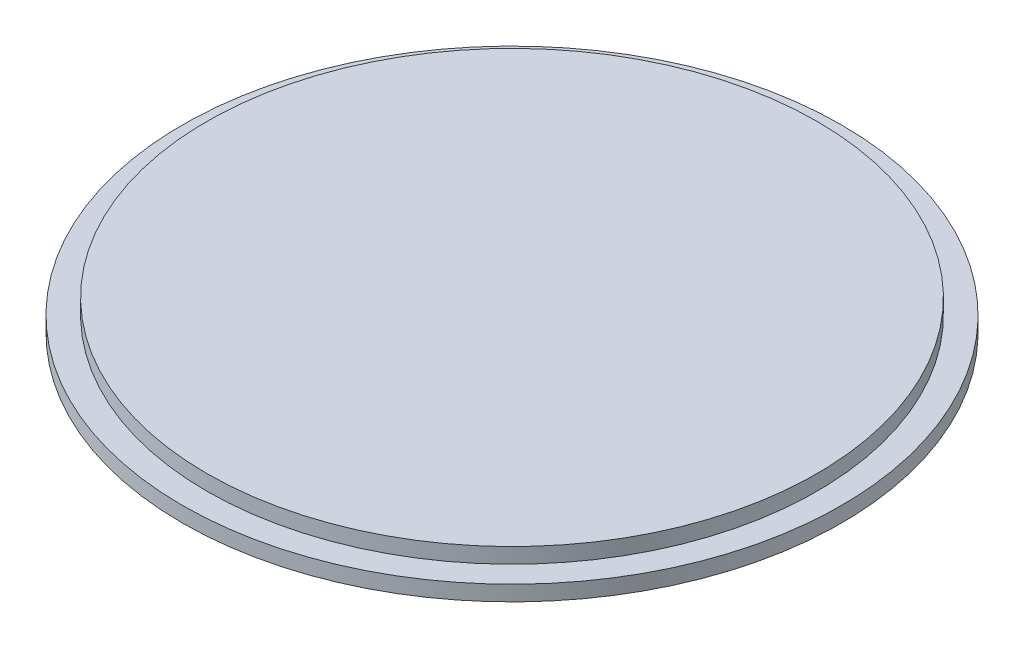
SolidWorks part; units mm, degrees
material "6061-T6 (SS)"
ref_plane "Front Plane" through (0, 0, 0) normal (0, 0, 1) x (1, 0, 0)
ref_plane "Top Plane" through (0, 0, 0) normal (0, 1, 0) x (1, 0, 0)
ref_plane "Right Plane" through (0, 0, 0) normal (1, 0, 0) x (0, 0, -1)
sketch "Sketch1" plane through (0, 0, 0) normal (0, 1, 0) x (1, 0, 0)
  circle A0 centre (0, 0) radius 68.326
  dimension "D1" = 136.652
extrude "Boss-Extrude1" add sketch "Sketch1" along normal blind 3.175
sketch "Sketch2" plane through (0, 3.175, 0) normal (0, 1, 0) x (1, 0, 0)
  circle A0 centre (0, 0) radius 63.246
  dimension "D1" = 126.492
extrude "Boss-Extrude2" add sketch "Sketch2" along normal blind 3.175
